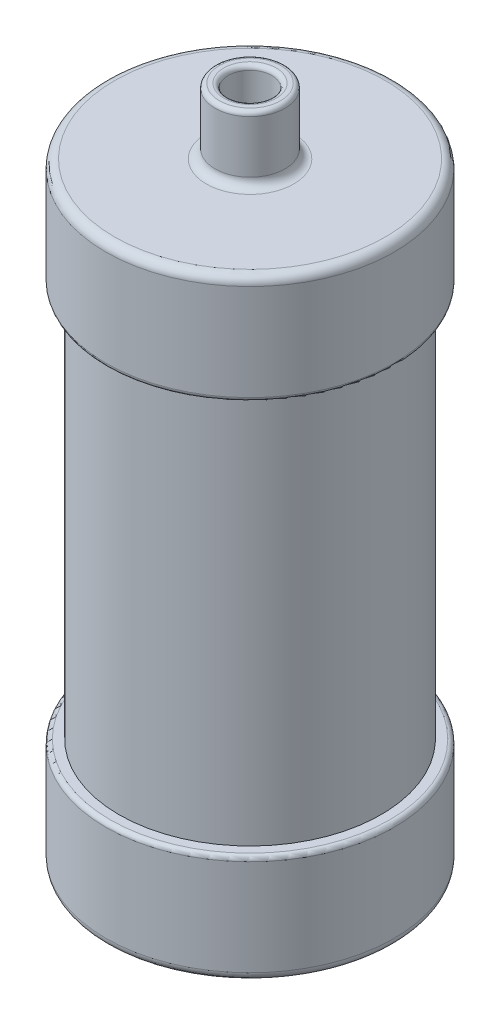
SolidWorks part; units mm, degrees
ref_plane "Alzado" through (0, 0, 0) normal (0, 0, 1) x (1, 0, 0)
ref_plane "Planta" through (0, 0, 0) normal (0, 1, 0) x (1, 0, 0)
ref_plane "Vista lateral" through (0, 0, 0) normal (1, 0, 0) x (0, 0, -1)
sketch "Croquis1" plane through (0, 0, 0) normal (0, 1, 0) x (1, 0, 0)
  circle A0 centre (0, 0) radius 30
  dimension "D1" = 60
extrude "Extruir-Lámina1" add sketch "Croquis1" along normal blind 60 and the other way blind 60 thin thin type one direction reverse wall 3
sketch "Croquis2" plane through (0, 60, 0) normal (0, 1, 0) x (1, 0, 0)
  circle A1 centre (0, 0) radius 30 construction
  circle A2 centre (0, 0) radius 33
  circle A3 centre (0, 0) radius 33
  circle A4 centre (0, 0) radius 30
  dimension "D1" = 3
extrude "Extruir1" add sketch "Croquis2" against normal blind 15 separate body
sketch "Croquis3" plane through (0, 60, 0) normal (0, 1, 0) x (1, 0, 0)
  circle A0 centre (0, 0) radius 33 construction
  circle A1 centre (0, 0) radius 33
extrude "Extruir2" add sketch "Croquis3" along normal blind 10
sketch "Croquis4" plane through (0, 70, 0) normal (0, 1, 0) x (1, 0, 0)
  circle A0 centre (0, 0) radius 5
  circle A1 centre (0, 0) radius 8
  dimension "D1" = 10
  dimension "D2" = 3
extrude "Extruir3" add sketch "Croquis4" along normal blind 15
sketch "Croquis5" plane through (0, 70, 0) normal (0, 1, 0) x (1, 0, 0)
  circle A0 centre (0, 0) radius 5 construction
  circle A1 centre (0, 0) radius 5
extrude "Extruir4" cut sketch "Croquis5" against normal blind 20
fillet "Redondeo1" radius 2 2 edges at (0, 70, 8) (0, 70, 33)
fillet "Redondeo2" radius 1 3 edges at (0, 45, 33) (0, 85, 5) (0, 85, 8)
mirror "Simetría1" about plane through (0, 0, 0) normal (0, 1, 0) of bodies 105
